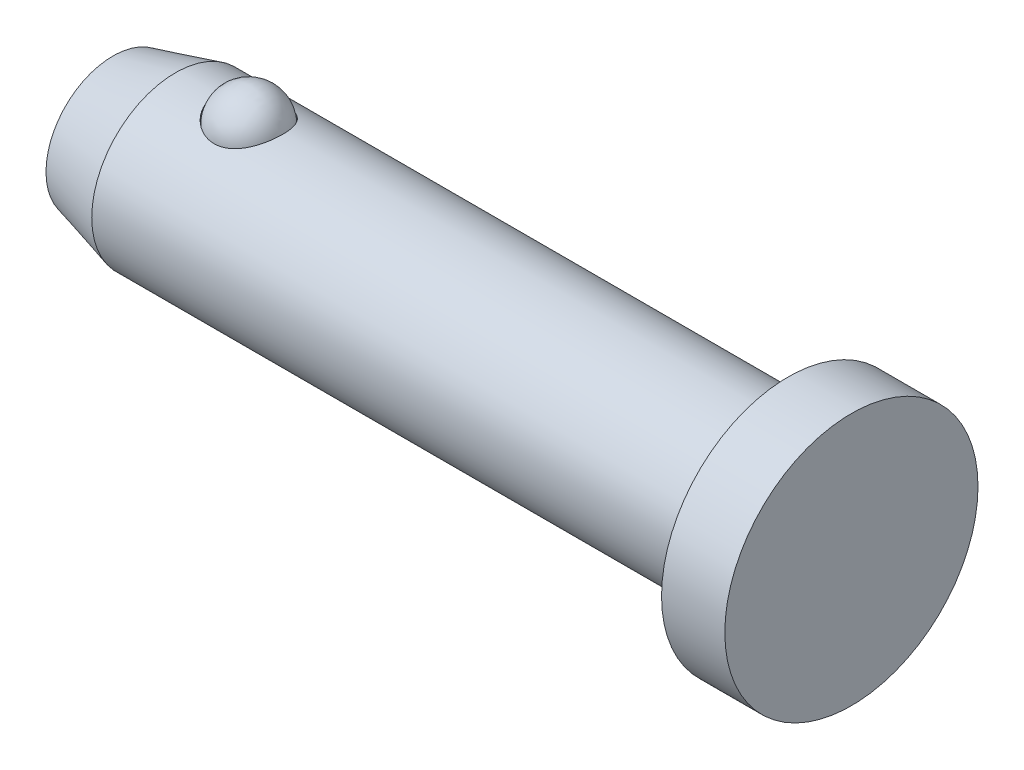
SolidWorks part; units mm, degrees
ref_plane "Front" through (0, 0, 0) normal (0, 0, 1) x (1, 0, 0)
ref_plane "Top" through (0, 0, 0) normal (0, 1, 0) x (1, 0, 0)
ref_plane "Right" through (0, 0, 0) normal (1, 0, 0) x (0, 0, -1)
sketch "Sketch1" plane through (0, 0, 0) normal (0, 0, 1) x (1, 0, 0)
  line L0 (2.3813, 4.7625) -> (0, 4.7625)
  line L1 (0, 3.1496) -> (0, 4.7625)
  line L4 (2.3813, 4.7625) -> (2.3813, 0)
  line L16 (0, 3.1496) -> (-23.0491, 3.1496)
  line L17 (-25.4, 3.1496) -> (-25.4, 2.5197) construction
  line L19 (-23.0491, 3.1496) -> (-25.4, 3.1496) construction
  line L22 (-25.4, -3.1496) -> (-23.0491, -3.1496) construction
  line L23 (-20.2908, 2.8346) -> (-20.2908, -2.8346) construction
  line L24 (-25.4, 0) -> (2.3813, 0)
  line L27 (2.3813, 0) -> (7.1437, 0) construction
  line L29 (-25.4, 0) -> (-25.4, -2.5197) construction
  line L36 (0, 0) -> (0, 3.1496) construction
  line L37 (-25.4, 2.5197) -> (-25.4, 0)
  line L38 (-23.0491, -3.1496) -> (2.3812, -3.1496) construction
  line L39 (-25.4, -2.5197) -> (-25.4, -3.1496) construction
  line L40 (-23.0491, 3.1496) -> (-25.4, 2.5197)
  line L42 (-23.0491, -3.1496) -> (-25.4, -2.5197) construction
  line L43 (-23.0491, 3.1496) -> (-23.0491, -3.1496) construction
  circle A2 centre (-20.2908, 2.8346) radius 1.2802 construction
  point P8 (-20.2908, 4.1148)
  point P9 (-19.05, 4.1148)
  point P35 (-19.05, 3.1496)
  dimension "D2" = 5.6693
  dimension "D11" = 0.9652
  dimension "A" = 6.2992
  dimension "E" = 7.2644
  dimension "Useable Length" = 19.05
  dimension "D12" = 5.0394
  dimension "A1" = 15
  dimension "Head Height" = 2.3813
  dimension "Length" = 25.4
  dimension "Head Dia" = 9.525
revolve "Revolve1" add sketch "Sketch1" angle 360 about L27
sketch "Sketch2" plane through (0, 0, 0) normal (0, 0, 1) x (1, 0, 0)
  line L0 (-18.9853, 2.8346) -> (-21.5964, 2.8346)
  line L1 (-20.2908, 4.1148) -> (-20.2908, 4.1402) construction
  line L2 (-18.9853, 2.8346) -> (-16.3741, 2.8346) construction
  circle A0 centre (-20.2908, 2.8346) radius 1.2802 construction
  circle A1 centre (-20.2908, 2.8346) radius 1.2802 construction
  arc A2 (-21.5964, 2.8346) -> (-18.9853, 2.8346) centre (-20.2908, 2.8346) cw
  dimension "D1" = 0.0254
revolve "Cut-Revolve1" cut sketch "Sketch2" angle 360 about L2
sketch "Sketch3" plane through (0, 0, 0) normal (0, 0, 1) x (1, 0, 0)
  line L0 (-19.0107, 2.8346) -> (-21.571, 2.8346)
  line L1 (-19.0107, 2.8346) -> (-16.4503, 2.8346) construction
  circle A0 centre (-20.2908, 2.8346) radius 1.2802 construction
  arc A1 (-19.0107, 2.8346) -> (-21.571, 2.8346) centre (-20.2908, 2.8346) ccw
revolve "Revolve2" add sketch "Sketch3" angle 360 about L1
equation "\"D12@Sketch1\"=\"A@Sketch1\" * 0.80"
equation "\"D2@Sketch1\"=\"A@Sketch1\" * 0.9"
